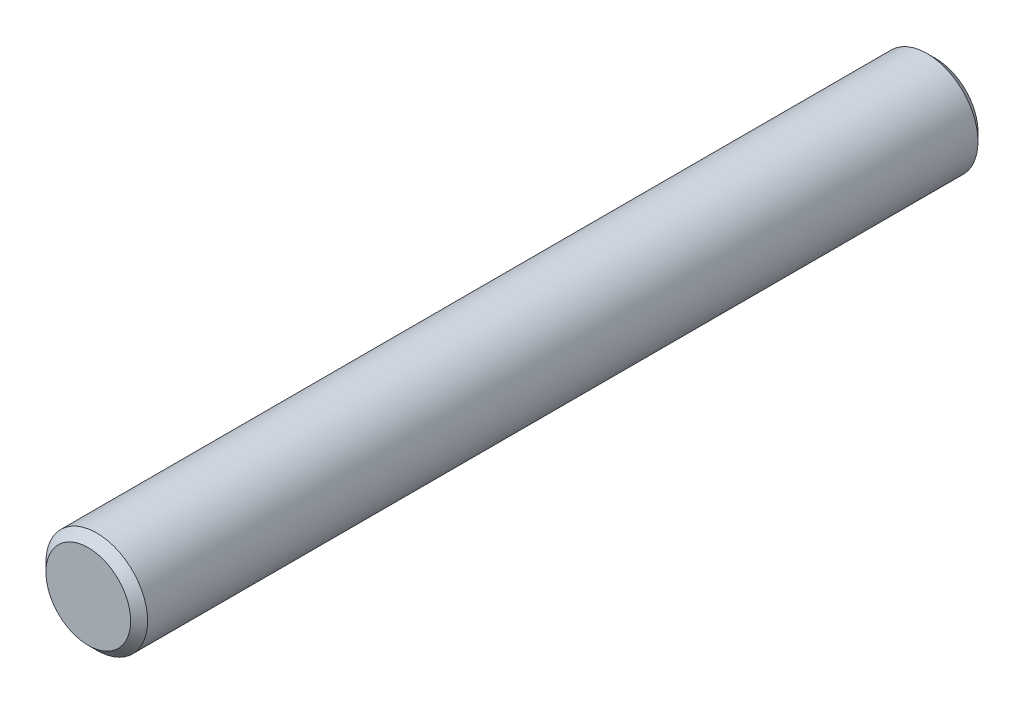
SolidWorks part; units mm, degrees
ref_plane "Front Plane" through (0, 0, 0) normal (0, 0, 1) x (1, 0, 0)
ref_plane "Top Plane" through (0, 0, 0) normal (0, 1, 0) x (1, 0, 0)
ref_plane "Right Plane" through (0, 0, 0) normal (1, 0, 0) x (0, 0, -1)
sketch "Sketch2" plane through (0, 0, 0) normal (0, 0, 1) x (1, 0, 0)
  circle A0 centre (0, 0) radius 1.5
  dimension "D1" = 3
extrude "Boss-Extrude1" add sketch "Sketch2" along normal mid plane 25
chamfer "Chamfer1" distance 0.25 angle 45 2 edges at (1.5, 0, -12.5) (1.5, 0, 12.5)
